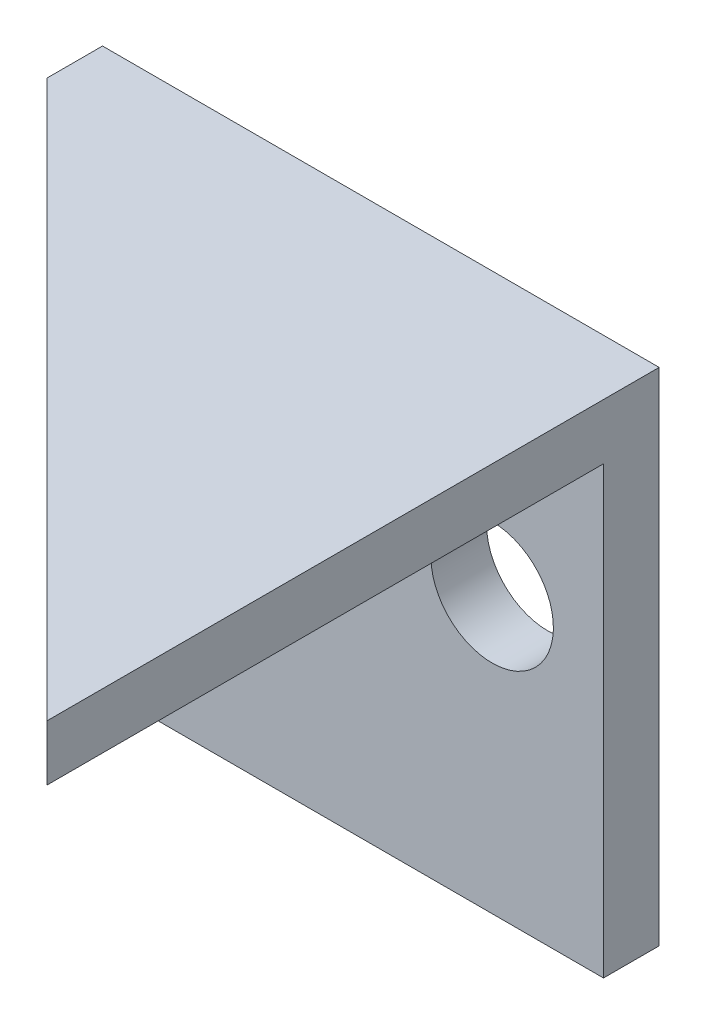
SolidWorks part; units mm, degrees
ref_plane "Front Plane" through (0, 0, 0) normal (0, 0, 1) x (1, 0, 0)
ref_plane "Top Plane" through (0, 0, 0) normal (0, 1, 0) x (1, 0, 0)
ref_plane "Right Plane" through (0, 0, 0) normal (1, 0, 0) x (0, 0, -1)
ref_plane "Plane1" through (0, 12, 0) normal (0, -1, 0) x (1, 0, 0)
sketch "Sketch1" plane through (0, 12, 0) normal (0, -1, 0) x (1, 0, 0)
  line L0 (15, 0) -> (15, 33)
  line L1 (15, 33) -> (-15, 3)
  line L2 (-15, 3) -> (-15, 0)
  line L3 (-15, 0) -> (15, 0)
extrude "Boss-Extrude1" add sketch "Sketch1" against normal blind 3
sketch "Sketch2" plane through (0, 12, 0) normal (0, -1, 0) x (1, 0, 0)
  line L0 (15, 3) -> (15, 0)
  line L1 (15, 0) -> (-15, 0)
  line L2 (-15, 0) -> (-15, 3)
  line L3 (-15, 3) -> (15, 3)
extrude "Boss-Extrude2" add sketch "Sketch2" along normal blind 24
sketch "Sketch5" plane through (0, 0, 0) normal (0, 0, -1) x (-1, 0, 0)
  line L0 (15, -12) -> (-15, -12) construction
  line L1 (-15, 15) -> (-15, -12) construction
  line L2 (15, 15) -> (15, -12) construction
  circle A0 centre (-9, 3) radius 3.3
  circle A1 centre (9, 3) radius 3.3
  dimension "D1" = 6.6
  dimension "D2" = 6.6
  dimension "D3" = 15
  dimension "D4" = 15
  dimension "D5" = 6
  dimension "D6" = 6
extrude "Cut-Extrude1" cut sketch "Sketch5" against normal blind 10
